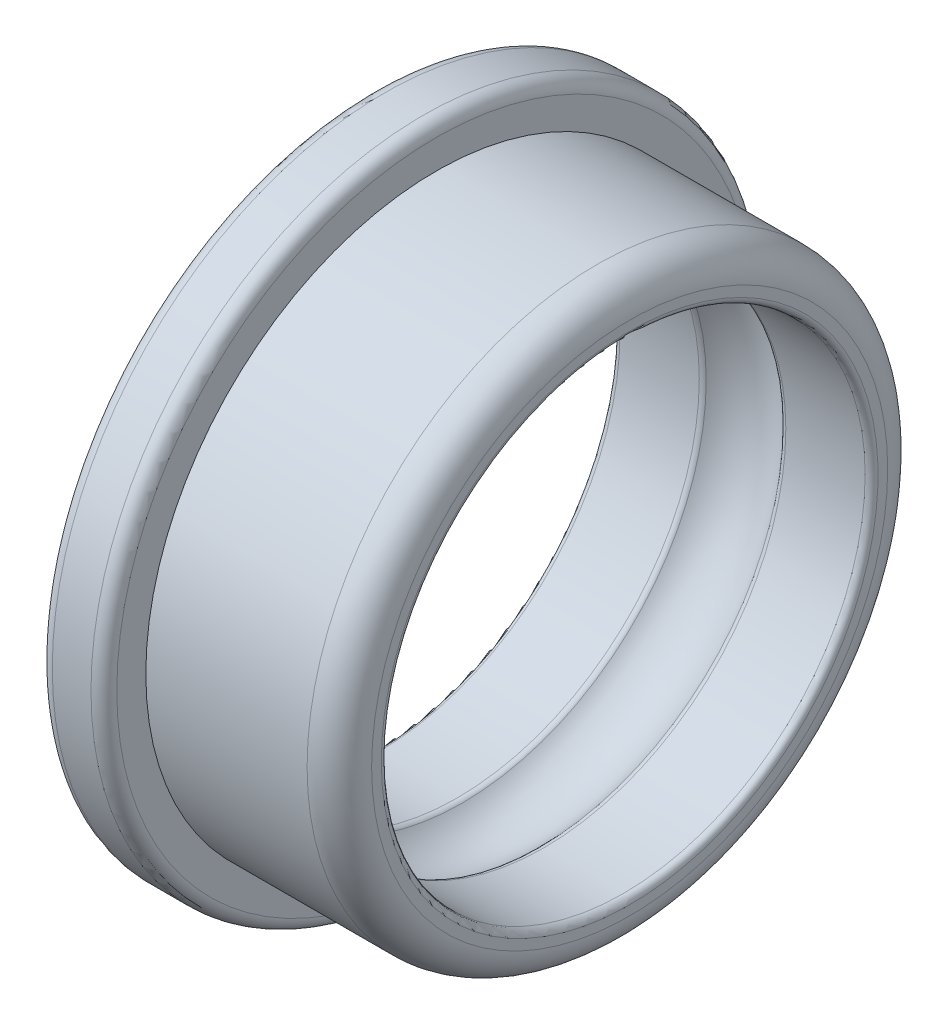
SolidWorks part; units mm, degrees
ref_plane "Front Plane" through (0, 0, 0) normal (0, 0, 1) x (1, 0, 0)
ref_plane "Top Plane" through (0, 0, 0) normal (0, 1, 0) x (1, 0, 0)
ref_plane "Right Plane" through (0, 0, 0) normal (1, 0, 0) x (0, 0, -1)
sketch "Sketch1" plane through (0, 0, 0) normal (0, 0, 1) x (1, 0, 0)
  line L0 (-66.6951, 0) -> (150.3544, 0) construction
  line L1 (0, 51.0243) -> (0, 0) construction
  line L2 (-10, 45) -> (20, 45)
  line L3 (-20, 45) -> (-20, 37.5)
  line L4 (-20, 37.5) -> (-6.245, 37.5)
  line L5 (20, 45) -> (20, 37.5)
  line L6 (-20, 45) -> (20, 37.5) construction
  line L7 (-20, 37.5) -> (20, 45) construction
  line L8 (6.245, 37.5) -> (20, 37.5)
  line L9 (-20, 45) -> (-20, 51.5)
  line L10 (-20, 51.5) -> (-10, 51.5)
  line L11 (-10, 51.5) -> (-10, 45)
  line L12 (-10, 45) -> (-20, 45) construction
  arc A0 (-6.245, 37.5) -> (6.245, 37.5) centre (0, 32.5) cw
  point P3 (0, 41.25)
  dimension "D5" = 8
  dimension "D1" = 40
  dimension "D2" = 37.5
  dimension "D3" = 45
  dimension "D4" = 5
  dimension "D6" = 51.5
  dimension "D7" = 10
revolve "Revolve1" add sketch "Sketch1" angle 360 about L0
fillet "Fillet1" radius 5 1 edges at (20, 0, 45)
fillet "Fillet2" radius 1 4 edges at (6.245, 0, 37.5) (20, 0, 37.5) (-20, 0, 37.5) (-6.245, 0, 37.5)
fillet "Fillet3" radius 2 2 edges at (-10, 0, 51.5) (-20, 0, 51.5)
scale "Scale1" scale about centroid uniform scaling yes scale factor 0.1
